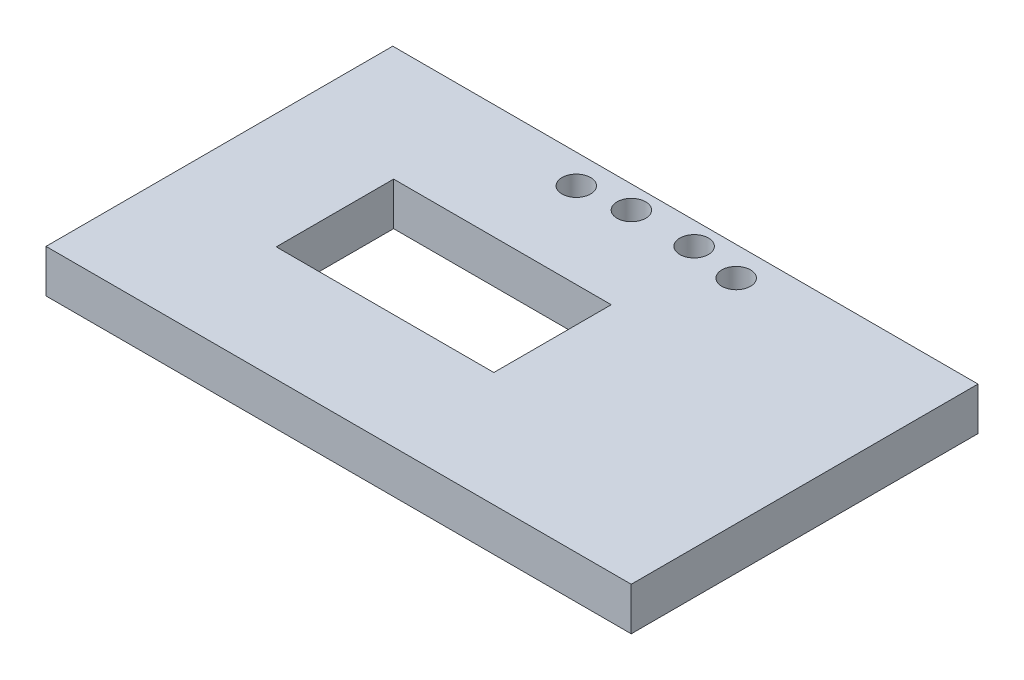
SolidWorks part; units mm, degrees
ref_plane "Front Plane" through (0, 0, 0) normal (0, 0, 1) x (1, 0, 0)
ref_plane "Top Plane" through (0, 0, 0) normal (0, 1, 0) x (1, 0, 0)
ref_plane "Right Plane" through (0, 0, 0) normal (1, 0, 0) x (0, 0, -1)
sketch "Sketch1" plane through (0, 0, 0) normal (0, 1, 0) x (1, 0, 0)
  line L1 (-30.658, -18.1659) -> (30.658, -18.1659)
  line L2 (-30.658, -18.1659) -> (-30.658, 18.1659)
  line L3 (-30.658, 18.1659) -> (30.658, 18.1659)
  line L4 (30.658, -18.1659) -> (30.658, 18.1659)
  line L5 (0, 18.1659) -> (0, -18.1659) construction
  line L6 (-30.658, 0) -> (30.658, 0) construction
  line L7 (4.2479, -6.15) -> (-18.5521, -6.15)
  line L8 (4.2479, -6.15) -> (4.2479, 6.15)
  line L9 (4.2479, 6.15) -> (-18.5521, 6.15)
  line L10 (-18.5521, -6.15) -> (-18.5521, 6.15)
  line L11 (-7.1521, 6.15) -> (-7.1521, -6.15) construction
  line L12 (4.2479, 0) -> (-18.5521, 0) construction
  circle A0 centre (-8.3756, 15.112) radius 1.5
  circle A1 centre (-3.2881, 15.796) radius 1.5
  circle A2 centre (3.2881, 15.796) radius 1.5
  circle A3 centre (8.3756, 15.112) radius 1.5
  point P0 (0, 0)
  point P6 (-7.1521, 0)
  point P16 (-21.7322, 27.9337)
  point P17 (-59.5052, -33.2956)
  point P18 (-15.4576, 29.4628)
  point P19 (-32.4676, 30.5259)
  point P20 (-7.5977, 29.0865)
  point P21 (-17.8619, 30.534)
  point P22 (-6.905, 15.0121)
  point P23 (-14.2703, 18.3002)
  point P24 (-13.5542, 14.0462)
  point P25 (-3.7979, 10.7816)
  point P26 (-11.2697, 14.5854)
  point P27 (-9.6222, 14.7677)
  point P28 (-7.7257, 15.308)
  point P29 (-9.7893, 11.9102)
  point P30 (-2.5745, 13.7705)
  point P31 (-3.1823, 12.3992)
  point P32 (-3.4689, 11.0785)
  point P33 (-8.3756, 15.112)
  point P34 (-3.2881, 15.796)
  dimension "D2" = 3
  dimension "D3" = 3
  dimension "D1" = 22.8
  dimension "D4" = 12.3
extrude "Boss-Extrude1" add sketch "Sketch1" along normal blind 4.5
sketch "Sketch2" plane through (0, 0, 0) normal (0, 1, 0) x (1, 0, 0)
  line L0 (-11.6401, 0) -> (-7.1521, 0) construction
  line L1 (-7.1521, 6.15) -> (-7.1521, -6.15) construction
  line L2 (4.2479, 6.15) -> (-18.5521, 6.15) construction
  line L3 (-18.5521, -6.15) -> (4.2479, -6.15) construction
  circle A0 centre (-11.6401, 0) radius 1.5
  point P2 (-4.041, 0)
  point P5 (-12.1403, 0)
  point P6 (-11.6401, 0)
  dimension "D1" = 3
